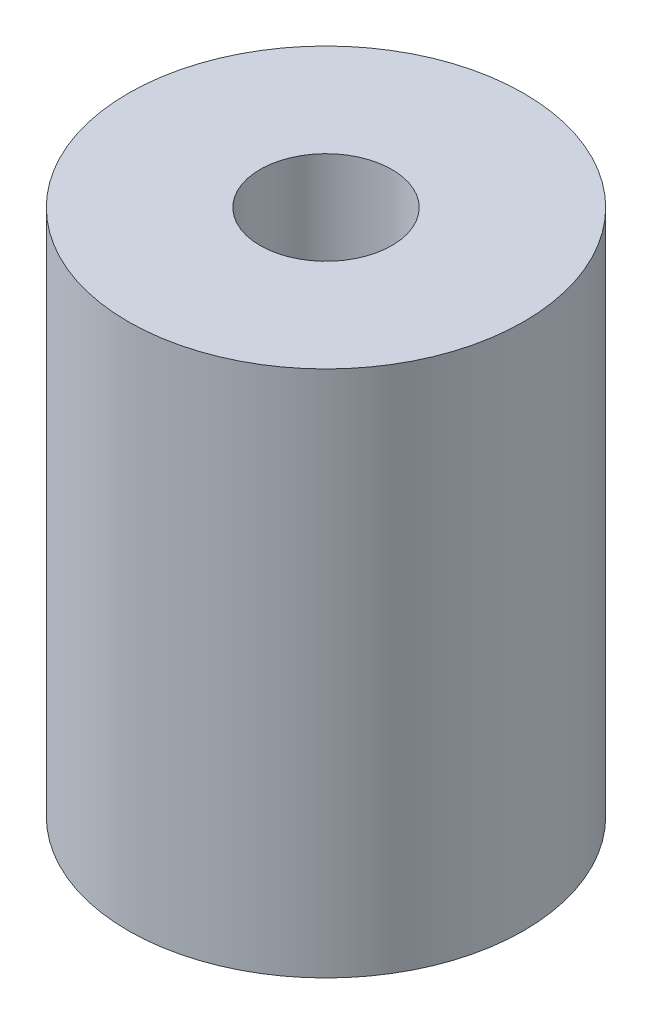
SolidWorks part; units mm, degrees
ref_plane "Front Plane" through (0, 0, 0) normal (0, 0, 1) x (1, 0, 0)
ref_plane "Top Plane" through (0, 0, 0) normal (0, 1, 0) x (1, 0, 0)
ref_plane "Right Plane" through (0, 0, 0) normal (1, 0, 0) x (0, 0, -1)
sketch "Sketch1" plane through (0, 0, 0) normal (0, 1, 0) x (1, 0, 0)
  circle A0 centre (0, 0) radius 7.5
  dimension "D1" = 15
extrude "Boss-Extrude1" add sketch "Sketch1" along normal blind 20
sketch "Sketch2" plane through (0, 20, 0) normal (0, 1, 0) x (1, 0, 0)
  circle A0 centre (0, 0) radius 2.5
  dimension "D1" = 5
extrude "Cut-Extrude1" cut sketch "Sketch2" against normal blind 10
sketch "Sketch3" plane through (0, 0, 0) normal (0, -1, 0) x (1, 0, 0)
  circle A0 centre (0, 0) radius 4
  dimension "D1" = 8
extrude "Cut-Extrude2" cut sketch "Sketch3" against normal blind 10
